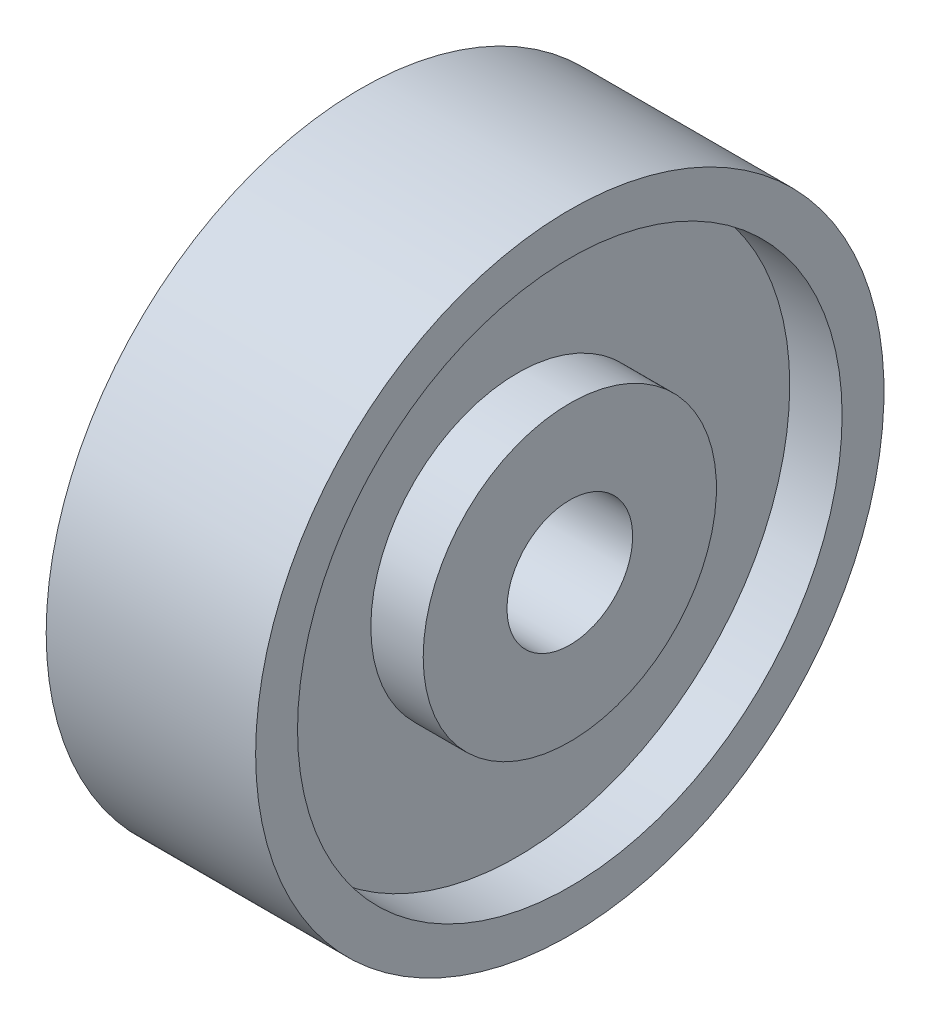
SolidWorks part; units mm, degrees
ref_plane "Front Plane" through (0, 0, 0) normal (0, 0, 1) x (1, 0, 0)
ref_plane "Top Plane" through (0, 0, 0) normal (0, 1, 0) x (1, 0, 0)
ref_plane "Right Plane" through (0, 0, 0) normal (1, 0, 0) x (0, 0, -1)
sketch "Sketch1" plane through (0, 0, 0) normal (0, 0, 1) x (1, 0, 0)
  line L0 (-5, 3) -> (5, 3)
  line L1 (5, 3) -> (5, 7)
  line L2 (5, 7) -> (2.5, 7)
  line L3 (2.5, 7) -> (2.5, 13)
  line L4 (2.5, 13) -> (5, 13)
  line L5 (5, 13) -> (5, 15)
  line L6 (5, 15) -> (-5, 15)
  line L7 (-5, 15) -> (-5, 13)
  line L8 (-5, 13) -> (-2.5, 13)
  line L9 (-2.5, 13) -> (-2.5, 7)
  line L10 (-2.5, 7) -> (-5, 7)
  line L11 (-5, 7) -> (-5, 3)
  line L12 (0, 179.712) -> (0, -176.456) construction
  line L13 (-265.4529, 0) -> (245.5708, 0) construction
  dimension "D1" = 3
  dimension "D2" = 10
  dimension "D3" = 30
  dimension "D4" = 4
  dimension "D5" = 10
  dimension "D6" = 2
  dimension "D7" = 5
revolve "Revolve1" add sketch "Sketch1" angle 360 about L13
